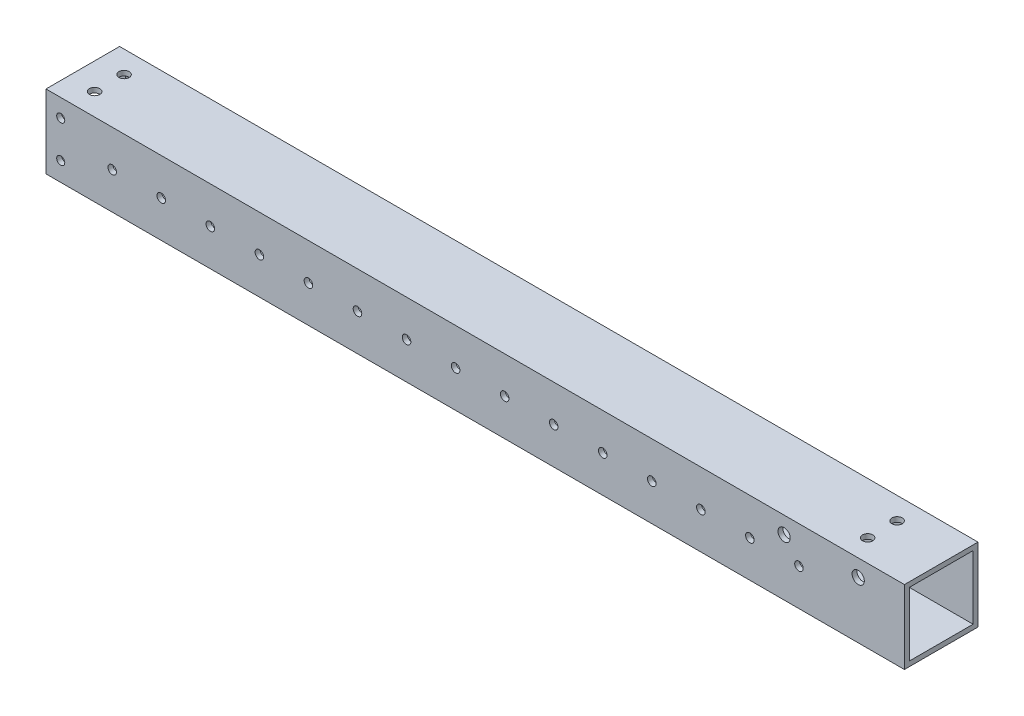
SolidWorks part; units mm, degrees
material "1060 合金"
ref_plane "前视基准面" through (0, 0, 0) normal (0, 0, 1) x (1, 0, 0)
ref_plane "上视基准面" through (0, 0, 0) normal (0, 1, 0) x (1, 0, 0)
ref_plane "右视基准面" through (0, 0, 0) normal (1, 0, 0) x (0, 0, -1)
sketch "草图1" plane through (0, 0, 0) normal (1, 0, 0) x (0, 0, -1)
  line L1 (-13, -13) -> (13, -13)
  line L2 (-13, -13) -> (-13, 13)
  line L3 (-13, 13) -> (13, 13)
  line L4 (13, -13) -> (13, 13)
  line L5 (-13, -13) -> (13, 13) construction
  line L6 (-13, 13) -> (13, -13) construction
  line L7 (-15, -15) -> (15, -15)
  line L8 (-15, -15) -> (-15, 15)
  line L9 (-15, 15) -> (15, 15)
  line L10 (15, -15) -> (15, 15)
  line L11 (-15, -15) -> (15, 15) construction
  line L12 (-15, 15) -> (15, -15) construction
  point P0 (0, 0)
  point P6 (0, 0)
  dimension "D1" = 30
  dimension "D2" = 30
  dimension "D3" = 2
extrude "凸台-拉伸1" add sketch "草图1" along normal blind 350
sketch "草图2" plane through (0, 0, -15) normal (0, 0, -1) x (-1, 0, 0)
  circle A0 centre (-307, 0) radius 1.75
  circle A1 centre (-287, 0) radius 1.75
  circle A2 centre (-267, 0) radius 1.75
  circle A3 centre (-247, 0) radius 1.75
  circle A4 centre (-227, 0) radius 1.75
  circle A5 centre (-207, 0) radius 1.75
  circle A6 centre (-187, 0) radius 1.75
  circle A7 centre (-167, 0) radius 1.75
  circle A8 centre (-147, 0) radius 1.75
  circle A9 centre (-127, 0) radius 1.75
  circle A10 centre (-107, 0) radius 1.75
  circle A11 centre (-87, 0) radius 1.75
  circle A12 centre (-67, 0) radius 1.75
  circle A13 centre (-47, 0) radius 1.75
  circle A14 centre (-27, 0) radius 1.75
extrude "切除-拉伸1" cut sketch "草图2" against normal through all
sketch "草图3" plane through (0, 0, 15) normal (0, 0, 1) x (1, 0, 0)
  circle A0 centre (6, 7.7249) radius 1.65
  circle A1 centre (6, -7.2751) radius 1.65
extrude "切除-拉伸2" cut sketch "草图3" against normal through all
sketch "草图4" plane through (0, 15, 0) normal (0, 1, 0) x (1, 0, 0)
  circle A0 centre (326, 6) radius 2.1
  circle A1 centre (326, -6) radius 2.1
extrude "切除-拉伸3" cut sketch "草图4" against normal through all
sketch "草图5" plane through (0, -15, 0) normal (0, -1, 0) x (1, 0, 0)
  circle A0 centre (10.8315, 6) radius 2.1
  circle A1 centre (10.8315, -6) radius 2.1
extrude "切除-拉伸4" cut sketch "草图5" against normal through all
sketch "草图6" plane through (0, 0, -15) normal (0, 0, -1) x (-1, 0, 0)
  circle A0 centre (-331.15, 8.1) radius 2.5
  circle A1 centre (-300.95, 8.1) radius 2.5
extrude "切除-拉伸5" cut sketch "草图6" against normal through all
